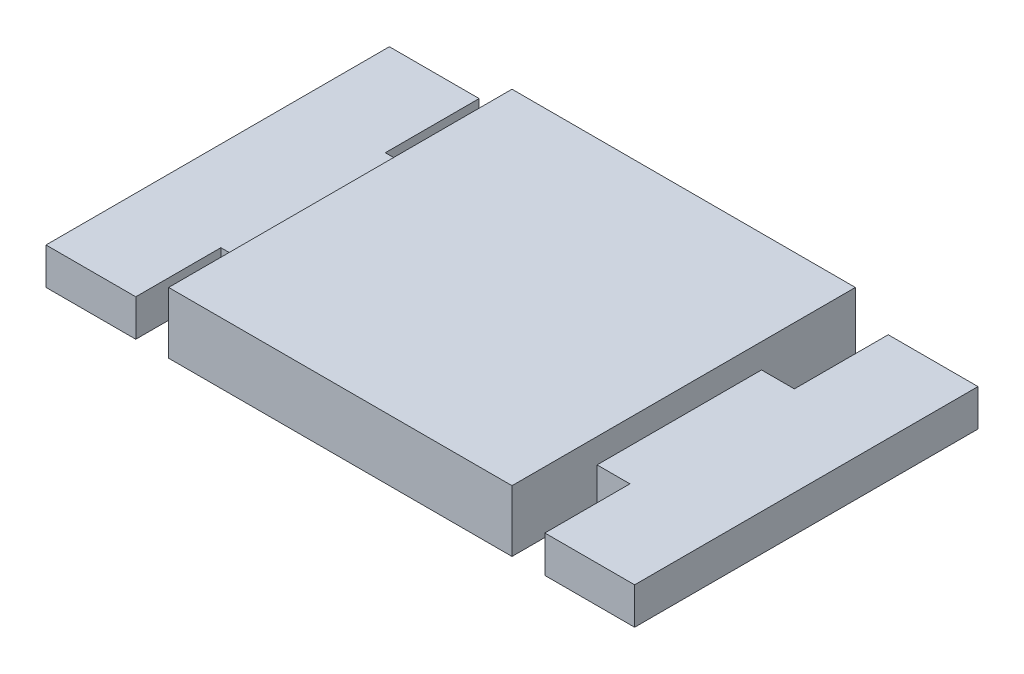
SolidWorks part; units mm, degrees
material "硅"
ref_plane "前视" through (0, 0, 0) normal (0, 0, 1) x (1, 0, 0)
ref_plane "上视" through (0, 0, 0) normal (0, 1, 0) x (1, 0, 0)
ref_plane "右视" through (0, 0, 0) normal (1, 0, 0) x (0, 0, -1)
sketch "草图2" plane through (0, 0, 0) normal (0, 1, 0) x (1, 0, 0)
  line L0 (0, 9.2839) -> (-2.679, 9.2839)
  line L1 (0, 16.9367) -> (28, 16.9367)
  line L2 (0, 16.9367) -> (0, 9.2839)
  line L3 (0, -11.0633) -> (28, -11.0633)
  line L4 (28, 16.9367) -> (28, 9.2839)
  line L5 (-2.679, 9.2839) -> (-2.679, 16.9367)
  line L6 (-2.679, 16.9367) -> (-10, 16.9367)
  line L7 (-10, 16.9367) -> (-10, -11.0633)
  line L8 (-10, -11.0633) -> (-2.679, -11.0633)
  line L9 (-2.679, -11.0633) -> (-2.679, -4.1251)
  line L10 (-2.679, -4.1251) -> (0, -4.1251)
  line L11 (14, 21.7682) -> (14, -13.9892) construction
  line L12 (30.679, -4.1251) -> (28, -4.1251)
  line L13 (30.679, -11.0633) -> (30.679, -4.1251)
  line L14 (38, -11.0633) -> (30.679, -11.0633)
  line L15 (38, 16.9367) -> (38, -11.0633)
  line L16 (30.679, 16.9367) -> (38, 16.9367)
  line L17 (30.679, 9.2839) -> (30.679, 16.9367)
  line L18 (28, 9.2839) -> (30.679, 9.2839)
  line L19 (0, -4.1251) -> (0, -11.0633)
  line L20 (28, -4.1251) -> (28, -11.0633)
  dimension "D1" = 28
  dimension "D2" = 28
  dimension "D3" = 10
extrude "凸台-拉伸1" add sketch "草图2" along normal blind 3
sketch "草图3" plane through (0, 3, 0) normal (0, 1, 0) x (1, 0, 0)
  line L0 (0, -11.0633) -> (28, -11.0633) construction
  line L1 (0, 16.9367) -> (28, 16.9367)
  line L2 (0, 16.9367) -> (0, -11.0633)
  line L3 (0, -11.0633) -> (28, -11.0633)
  line L4 (28, 16.9367) -> (28, -11.0633)
extrude "凸台-拉伸2" add sketch "草图3" along normal blind 1
sketch "草图4" plane through (0, 4, 0) normal (0, 1, 0) x (1, 0, 0)
  line L1 (0, 16.9367) -> (28, 16.9367)
  line L2 (0, 16.9367) -> (0, -11.0633)
  line L3 (0, -11.0633) -> (28, -11.0633)
  line L4 (28, 16.9367) -> (28, -11.0633)
extrude "凸台-拉伸3" add sketch "草图4" along normal blind 1
